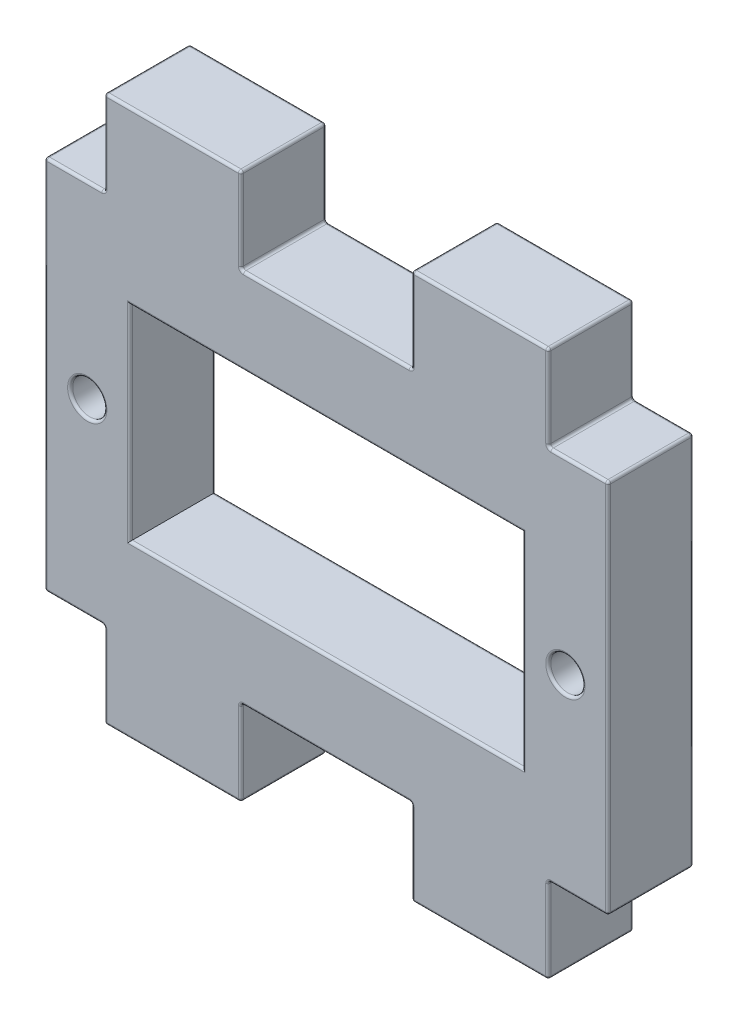
SolidWorks part; units mm, degrees
ref_plane "Front Plane" through (0, 0, 0) normal (0, 0, 1) x (1, 0, 0)
ref_plane "Top Plane" through (0, 0, 0) normal (0, 1, 0) x (1, 0, 0)
ref_plane "Right Plane" through (0, 0, 0) normal (1, 0, 0) x (0, 0, -1)
sketch "Sketch1" plane through (0, 0, 0) normal (0, 0, 1) x (1, 0, 0)
  line L0 (-16.5, 11) -> (16.5, 11)
  line L1 (-11.5, -6) -> (11.5, -6)
  line L2 (-11.5, -6) -> (-11.5, 6)
  line L3 (-11.5, 6) -> (11.5, 6)
  line L4 (11.5, -6) -> (11.5, 6)
  line L5 (-11.5, -6) -> (11.5, 6) construction
  line L6 (-11.5, 6) -> (11.5, -6) construction
  line L7 (16.5, -11) -> (16.5, 11)
  line L8 (-16.5, -11) -> (16.5, -11)
  line L9 (-16.5, -11) -> (-16.5, 11)
  line L10 (0, 0) -> (0, 24.3825) construction
  line L11 (-13, 11) -> (-5, 11)
  line L12 (-13, 11) -> (-13, 16)
  line L13 (-13, 16) -> (-5, 16)
  line L14 (-5, 11) -> (-5, 16)
  line L15 (13, 11) -> (13, 16)
  line L16 (13, 16) -> (5, 16)
  line L17 (5, 11) -> (5, 16)
  line L18 (13, 11) -> (5, 11)
  line L19 (0, 0) -> (29.239, 0) construction
  line L20 (13, -11) -> (5, -11)
  line L21 (5, -11) -> (5, -16)
  line L22 (13, -16) -> (5, -16)
  line L23 (13, -11) -> (13, -16)
  line L24 (-5, -11) -> (-5, -16)
  line L25 (-13, -16) -> (-5, -16)
  line L26 (-13, -11) -> (-13, -16)
  line L27 (-13, -11) -> (-5, -11)
  circle A0 centre (14, 0) radius 1
  circle A1 centre (-14, 0) radius 1
  point P0 (0, 0)
  dimension "D7" = 2
  dimension "D1" = 12
  dimension "D2" = 23
  dimension "D4" = 3.5
  dimension "D5" = 5
  dimension "D6" = 8
  dimension "D8" = 2.5
  dimension "D3" = 5
extrude "Boss-Extrude1" add sketch "Sketch1" along normal blind 5 contours L0 L14 L13 L12 | L17 L0 L15 L16 | L9 L8 L7 L0 L4 L1 L2 L3 A0 A1 | L23 L8 L21 L22 | L8 L26 L25 L24
fillet "Fillet1" radius 0.15 60 edges at (-13, -16, 2.5) (-13, -13.5, 0) (-9, -16, 0) (-13, -13.5, 5) (-13, -11, 2.5) (-5, -16, 2.5) (-9, -16, 5) (-14.75, -11, 0) (-5, -13.5, 0) (-14.75, -11, 5) (-16.5, -11, 2.5) (-5, -13.5, 5) (-5, -11, 2.5) (-16.5, 0, 0) (0, -11, 0) (-16.5, 0, 5) (-16.5, 11, 2.5) (5, -11, 2.5) (0, -11, 5) (-14.75, 11, 0) (5, -13.5, 0) (-14.75, 11, 5) (-13, 11, 2.5) (5, -16, 2.5) (5, -13.5, 5) (-13, 13.5, 0) (9, -16, 0) (-13, 13.5, 5) (-13, 16, 2.5) (9, -16, 5) (13, -16, 2.5) (-9, 16, 0) (13, -13.5, 0) (-9, 16, 5) (-5, 16, 2.5) (13, -13.5, 5) (13, -11, 2.5) (-5, 13.5, 0) (14.75, -11, 0) (-5, 13.5, 5) (-5, 11, 2.5) (16.5, -11, 2.5) (14.75, -11, 5) (0, 11, 0) (16.5, 0, 0) (0, 11, 5) (5, 11, 2.5) (16.5, 11, 2.5) (16.5, 0, 5) (5, 13.5, 0) (14.75, 11, 0) (5, 13.5, 5) (5, 16, 2.5) (14.75, 11, 5) (13, 11, 2.5) (9, 16, 0) (13, 13.5, 0) (9, 16, 5) (13, 13.5, 5) (13, 16, 2.5)
fillet "Fillet2" radius 0.15 12 edges at (0, -6, 0) (-11.5, 0, 0) (0, 6, 0) (11.5, 0, 0) (15, 0, 0) (-13, 0, 0) (-13, 0, 5) (15, 0, 5) (0, 6, 5) (-11.5, 0, 5) (0, -6, 5) (11.5, 0, 5)
